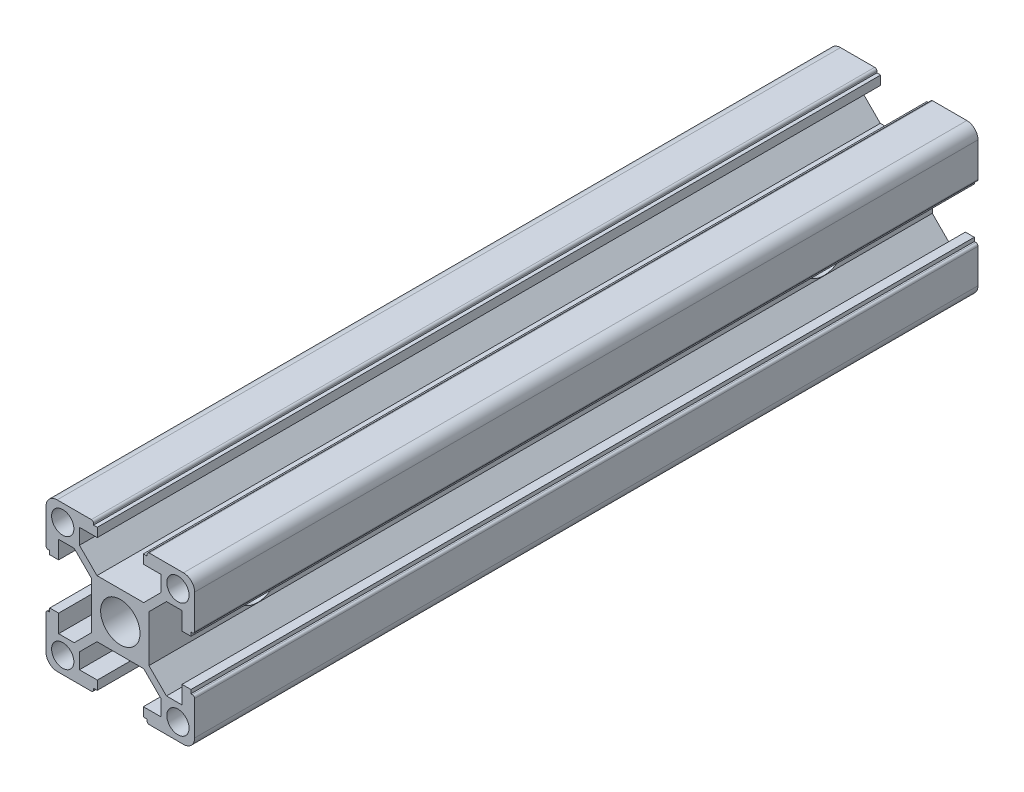
SolidWorks part; units mm, degrees
ref_plane "前视基准面" through (0, 0, 0) normal (0, 0, 1) x (1, 0, 0)
ref_plane "上视基准面" through (0, 0, 0) normal (0, 1, 0) x (1, 0, 0)
ref_plane "右视基准面" through (0, 0, 0) normal (1, 0, 0) x (0, 0, -1)
sketch "草图1" plane through (0, 0, 0) normal (0, 0, 1) x (1, 0, 0)
  line L0 (-7.75, 0) -> (0, 0) construction
  line L1 (7.75, -7.75) -> (-7.75, -7.75) construction
  line L2 (7.75, -7.75) -> (7.75, 7.75) construction
  line L3 (7.75, 7.75) -> (-7.75, 7.75) construction
  line L4 (-7.75, -7.75) -> (-7.75, 7.75) construction
  line L5 (7.75, -7.75) -> (-7.75, 7.75) construction
  line L6 (7.75, 7.75) -> (-7.75, -7.75) construction
  line L7 (0, 0) -> (0, 7.75) construction
  line L8 (3.1429, 3.85) -> (-3.1429, 3.85)
  line L9 (-3.1429, 3.85) -> (-5.5, 6.2071)
  line L10 (-5.5, 6.2071) -> (-5.5, 8.3)
  line L11 (-5.5, 8.3) -> (-3.1, 8.3)
  line L12 (-3.1, 8.3) -> (-3.1, 9.5)
  line L13 (-3.1, 9.5) -> (-3.6, 9.5)
  line L14 (-3.6, 9.5) -> (-3.6, 9.7)
  line L15 (-3.9, 10) -> (-8.5, 10)
  line L16 (-3.85, -3.1429) -> (-3.85, 3.1429)
  line L17 (-3.85, 3.1429) -> (-6.2071, 5.5)
  line L18 (-6.2071, 5.5) -> (-8.3, 5.5)
  line L19 (-8.3, 5.5) -> (-8.3, 3.1)
  line L20 (-9.5, 3.1) -> (-9.5, 3.6)
  line L21 (-8.3, 3.1) -> (-9.5, 3.1)
  line L22 (-9.5, 3.6) -> (-9.7, 3.6)
  line L23 (-10, 3.9) -> (-10, 8.5)
  line L24 (5.5, 8.3) -> (3.1, 8.3)
  line L25 (3.6, 9.5) -> (3.6, 9.7)
  line L26 (3.1, 9.5) -> (3.6, 9.5)
  line L27 (3.1, 8.3) -> (3.1, 9.5)
  line L28 (5.5, 6.2071) -> (5.5, 8.3)
  line L29 (3.1429, 3.85) -> (5.5, 6.2071)
  line L30 (3.85, -3.1429) -> (3.85, 3.1429)
  line L31 (3.85, 3.1429) -> (6.2071, 5.5)
  line L32 (9.5, 3.6) -> (9.7, 3.6)
  line L33 (8.3, 3.1) -> (9.5, 3.1)
  line L34 (9.5, 3.1) -> (9.5, 3.6)
  line L35 (8.3, 5.5) -> (8.3, 3.1)
  line L36 (6.2071, 5.5) -> (8.3, 5.5)
  line L37 (10, 3.9) -> (10, 8.5)
  line L38 (3.9, 10) -> (8.5, 10)
  line L39 (-9.5, -3.6) -> (-9.7, -3.6)
  line L40 (-8.3, -3.1) -> (-9.5, -3.1)
  line L41 (-9.5, -3.1) -> (-9.5, -3.6)
  line L42 (-8.3, -5.5) -> (-8.3, -3.1)
  line L43 (-6.2071, -5.5) -> (-8.3, -5.5)
  line L44 (-3.85, -3.1429) -> (-6.2071, -5.5)
  line L45 (-3.1429, -3.85) -> (-5.5, -6.2071)
  line L46 (-5.5, -6.2071) -> (-5.5, -8.3)
  line L47 (-3.6, -9.5) -> (-3.6, -9.7)
  line L48 (-3.1, -9.5) -> (-3.6, -9.5)
  line L49 (-3.1, -8.3) -> (-3.1, -9.5)
  line L50 (-5.5, -8.3) -> (-3.1, -8.3)
  line L51 (5.5, -6.2071) -> (5.5, -8.3)
  line L52 (3.1, -8.3) -> (3.1, -9.5)
  line L53 (3.1, -9.5) -> (3.6, -9.5)
  line L54 (3.6, -9.5) -> (3.6, -9.7)
  line L55 (5.5, -8.3) -> (3.1, -8.3)
  line L56 (3.1429, -3.85) -> (5.5, -6.2071)
  line L57 (3.1429, -3.85) -> (-3.1429, -3.85)
  line L58 (3.85, -3.1429) -> (6.2071, -5.5)
  line L59 (6.2071, -5.5) -> (8.3, -5.5)
  line L60 (8.3, -5.5) -> (8.3, -3.1)
  line L61 (9.5, -3.1) -> (9.5, -3.6)
  line L62 (8.3, -3.1) -> (9.5, -3.1)
  line L63 (9.5, -3.6) -> (9.7, -3.6)
  line L64 (3.9, -10) -> (8.5, -10)
  line L65 (10, -3.9) -> (10, -8.5)
  line L66 (-10, -3.9) -> (-10, -8.5)
  line L67 (-3.9, -10) -> (-8.5, -10)
  circle A0 centre (0, 0) radius 2.65
  circle A1 centre (-7.75, 7.75) radius 1.5
  circle A2 centre (7.75, 7.75) radius 1.5
  circle A3 centre (7.75, -7.75) radius 1.5
  circle A4 centre (-7.75, -7.75) radius 1.5
  arc A5 (-10, -8.5) -> (-8.5, -10) centre (-8.5, -8.5) ccw
  arc A6 (8.5, -10) -> (10, -8.5) centre (8.5, -8.5) ccw
  arc A7 (10, 8.5) -> (8.5, 10) centre (8.5, 8.5) ccw
  arc A8 (-8.5, 10) -> (-10, 8.5) centre (-8.5, 8.5) ccw
  arc A9 (3.6, -9.7) -> (3.9, -10) centre (3.9, -9.7) ccw
  arc A10 (-3.6, -9.7) -> (-3.9, -10) centre (-3.9, -9.7) cw
  arc A11 (-9.7, -3.6) -> (-10, -3.9) centre (-9.7, -3.9) ccw
  arc A12 (9.7, -3.6) -> (10, -3.9) centre (9.7, -3.9) cw
  arc A13 (9.7, 3.6) -> (10, 3.9) centre (9.7, 3.9) ccw
  arc A14 (-9.7, 3.6) -> (-10, 3.9) centre (-9.7, 3.9) cw
  arc A15 (3.6, 9.7) -> (3.9, 10) centre (3.9, 9.7) cw
  arc A16 (-3.6, 9.7) -> (-3.9, 10) centre (-3.9, 9.7) ccw
  point P46 (0, 3.85)
  point P56 (-3.85, 0)
  point P78 (3.85, 0)
  point P87 (-10, -10)
  point P90 (10, -10)
  point P93 (10, 10)
  point P96 (-10, 10)
  point P99 (3.6, -10)
  point P102 (-3.6, -10)
  point P105 (-10, -3.6)
  point P108 (10, -3.6)
  point P111 (10, 3.6)
  point P114 (-10, 3.6)
  point P117 (3.6, 10)
  point P120 (-3.6, 10)
  dimension "D1" = 5.3
  dimension "D2" = 3
  dimension "D11" = 1.5
  dimension "D12" = 2.25
  dimension "D13" = 0.3
  dimension "D3" = 7.7
  dimension "D4" = 6.2
  dimension "D5" = 1.7
  dimension "D6" = 1.2
  dimension "D7" = 20
  dimension "D8" = 7.2
  dimension "D9" = 11
  dimension "D10" = 1
extrude "凸台-拉伸1" add sketch "草图1" along normal mid plane 105.4
sketch "草图4" plane through (3.85, 0, 0) normal (1, 0, 0) x (0, 0, -1)
  line L0 (38.1, 0) -> (-38.1, 0) construction
  line L1 (-52.7, -3.1429) -> (-52.7, 3.1429) construction
  circle A0 centre (-38.1, 0) radius 3.1
  circle A1 centre (38.1, 0) radius 3.1
  point P4 (0, 0)
  dimension "D1" = 6.2
  dimension "D2" = 14.6
extrude "切除-拉伸3" cut sketch "草图4" against normal through all
